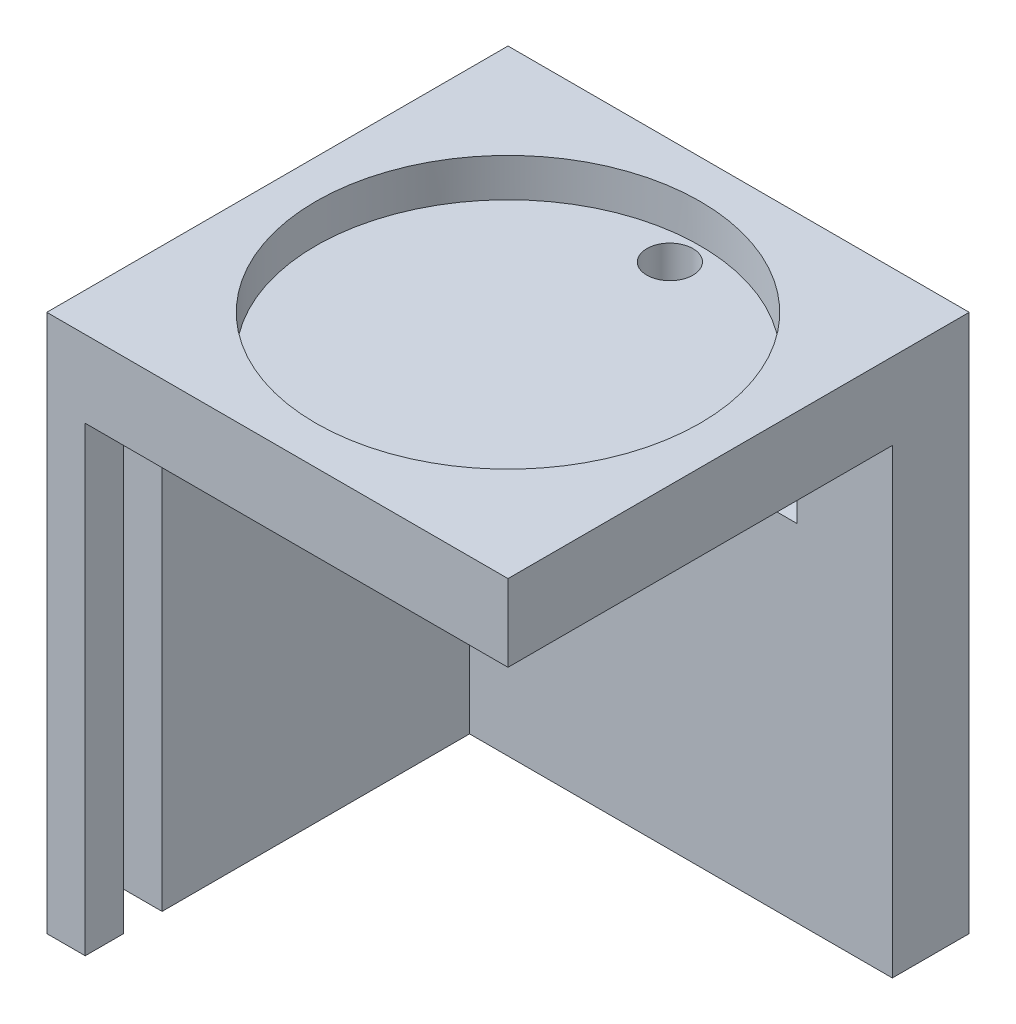
SolidWorks part; units mm, degrees
ref_plane "정면" through (0, 0, 0) normal (0, 0, 1) x (1, 0, 0)
ref_plane "윗면" through (0, 0, 0) normal (0, 1, 0) x (1, 0, 0)
ref_plane "우측면" through (0, 0, 0) normal (1, 0, 0) x (0, 0, -1)
sketch "Sketch1" plane through (0, 0, 0) normal (0, 1, 0) x (1, 0, 0)
  line L1 (0, 0) -> (670, 0)
  line L2 (0, 0) -> (0, 120)
  line L3 (0, 120) -> (670, 120)
  line L4 (670, 0) -> (670, 120)
  dimension "700" = 670
  dimension "D2" = 120
extrude "Boss-Extrude1" add sketch "Sketch1" along normal blind 530
sketch "Sketch2" plane through (0, 0, 0) normal (0, 0, 1) x (1, 0, 0)
  line L0 (0, 530) -> (0, 0) construction
  line L1 (10, 280) -> (110, 280)
  line L2 (10, 280) -> (10, 480)
  line L3 (10, 480) -> (110, 480)
  line L4 (110, 280) -> (110, 480)
  line L5 (0, 0) -> (670, 0) construction
  line L6 (120, 280) -> (120, 480)
  line L7 (120, 280) -> (220, 280)
  line L8 (220, 280) -> (220, 480)
  line L9 (120, 480) -> (220, 480)
  line L10 (230, 280) -> (230, 480)
  line L11 (230, 280) -> (330, 280)
  line L12 (330, 280) -> (330, 480)
  line L13 (230, 480) -> (330, 480)
  line L14 (340, 280) -> (340, 480)
  line L15 (340, 280) -> (440, 280)
  line L16 (440, 280) -> (440, 480)
  line L17 (340, 480) -> (440, 480)
  line L18 (450, 280) -> (450, 480)
  line L19 (450, 280) -> (550, 280)
  line L20 (550, 280) -> (550, 480)
  line L21 (450, 480) -> (550, 480)
  line L22 (560, 280) -> (560, 480)
  line L23 (560, 280) -> (660, 280)
  line L24 (660, 280) -> (660, 480)
  line L25 (560, 480) -> (660, 480)
  line L27 (10, 10) -> (660, 10)
  line L28 (10, 10) -> (10, 260)
  line L29 (10, 260) -> (660, 260)
  line L30 (660, 10) -> (660, 260)
  line L31 (0, 530) -> (670, 530) construction
  point P6 (10, 380)
  dimension "D1" = 100
  dimension "D2" = 200
  dimension "D3" = 10
  dimension "D4" = 50
  dimension "D6" = 10
  dimension "D7" = 20
  dimension "D5" = 6
extrude "Cut-Extrude1" cut sketch "Sketch2" against normal blind 100
sketch "Sketch3" plane through (0, 530, 0) normal (0, 1, 0) x (1, 0, 0)
  line L1 (670, 120) -> (0, 120) construction
  line L2 (0, 120) -> (0, 0) construction
  circle A0 centre (60, 60) radius 50
  circle A1 centre (170, 60) radius 50
  circle A2 centre (280, 60) radius 50
  circle A3 centre (390, 60) radius 50
  circle A4 centre (500, 60) radius 50
  circle A5 centre (610, 60) radius 50
  dimension "D1" = 100
  dimension "D2" = 10
  dimension "D3" = 10
  dimension "D4" = 6
extrude "Cut-Extrude2" cut sketch "Sketch3" against normal blind 260
hole_wizard "Ø12.0 (12) Diameter Hole2" positions "3DSketch1" profile "Sketch7" hole size "Ø12.0" standard "Ansi Metric"
sketch3d "3DSketch1"
  point P0 (59.7046, 270, -102.4117)
  point P2 (171.5567, 270, -102.6076)
  point P4 (280.8723, 270, -102.3969)
  point P6 (391.0687, 270, -102.7535)
  point P8 (500.7133, 270, -101.754)
  point P10 (609.5165, 270, -101.1227)
sketch "Sketch7" plane through (59.7046, 270, -102.4117) normal (1, 0, 0) x (0, 0, 1)
  line L0 (0, 0) -> (0, 33.6052)
  line L1 (0, 33.6052) -> (6, 30)
  line L2 (6, 30) -> (6, 0)
  line L5 (6, 0) -> (0, 0)
  line L10 (0, 33.6052) -> (-6, 30) construction
  line L11 (0, -6.35) -> (0, 107.95) construction
  dimension "구멍 지름" = 12
  dimension "구멍 깊이" = 30
  dimension "드릴 각도" = 118
sketch "Sketch8" plane through (0, 0, 0) normal (0, 0, 1) x (1, 0, 0)
  line L0 (660, 280) -> (660, 480) construction
  line L1 (10, 280) -> (660, 280)
  line L2 (10, 280) -> (10, 330)
  line L3 (10, 330) -> (660, 330)
  line L4 (660, 280) -> (660, 330)
  dimension "D1" = 50
extrude "Boss-Extrude2" add sketch "Sketch8" against normal blind 5
sketch "Sketch9" plane through (670, 0, 0) normal (1, 0, 0) x (0, 0, -1)
  line L0 (0, 530) -> (0, 0) construction
  line L1 (10, 10) -> (20, 10)
  line L2 (10, 10) -> (10, 260)
  line L3 (10, 260) -> (20, 260)
  line L4 (20, 10) -> (20, 260)
  line L5 (0, 0) -> (120, 0) construction
  dimension "D1" = 10
  dimension "D2" = 10
  dimension "D3" = 10
  dimension "D4" = 250
extrude "Cut-Extrude3" cut sketch "Sketch9" against normal blind 717
sketch "Sketch10" plane through (0, 10, 0) normal (0, 1, 0) x (1, 0, 0)
  line L0 (670, 120) -> (0, 120) construction
  line L1 (365, 61.9436) -> (350, 87.9243)
  line L2 (350, 87.9243) -> (320, 87.9243)
  line L3 (320, 87.9243) -> (305, 61.9436)
  line L4 (305, 61.9436) -> (320, 35.9628)
  line L5 (320, 35.9628) -> (350, 35.9628)
  line L6 (350, 35.9628) -> (365, 61.9436)
  line L7 (0, 120) -> (0, 0) construction
  circle A0 centre (335, 61.9436) radius 25.9808 construction
  dimension "D1" = 60
  dimension "D2" = 305
extrude "Cut-Extrude4" cut sketch "Sketch10" against normal blind 5
sketch "Sketch11" plane through (0, 0, -100) normal (0, 0, 1) x (1, 0, 0)
  line L0 (10, 10) -> (660, 10) construction
  line L1 (250, 10) -> (260, 10)
  line L2 (250, 10) -> (250, 110)
  line L3 (250, 110) -> (260, 110)
  line L4 (260, 10) -> (260, 110)
  line L5 (660, 10) -> (660, 260) construction
  line L6 (410, 10) -> (420, 10)
  line L7 (410, 10) -> (410, 110)
  line L8 (410, 110) -> (420, 110)
  line L9 (420, 10) -> (420, 110)
  line L10 (25, 198.4569) -> (325, 145.5588)
  line L11 (325, 145.5588) -> (325, 122.0178)
  line L12 (325, 122.0178) -> (345, 122.0178)
  line L13 (345, 122.0178) -> (345, 145.5588)
  line L14 (345, 145.5588) -> (645, 198.4569)
  line L15 (645, 198.4569) -> (25, 198.4569)
  point P18 (345, 133.7883)
  dimension "D1" = 10
  dimension "D2" = 10
  dimension "D3" = 100
  dimension "D4" = 100
  dimension "D5" = 150
  dimension "D6" = 240
  dimension "D7" = 20
  dimension "D8" = 65
  dimension "D9" = 100
  dimension "D10" = 620
  dimension "D11" = 100
extrude "Boss-Extrude3" add sketch "Sketch11" along normal blind 78 separate body
sketch "Sketch12" plane through (0, 0, -100) normal (0, 0, 1) x (1, 0, 0)
  line L0 (660, 260) -> (10, 260) construction
  line L1 (75.1986, 260) -> (95.1986, 260)
  line L2 (75.1986, 260) -> (75.1986, 230)
  line L3 (75.1986, 230) -> (95.1986, 230)
  line L4 (95.1986, 260) -> (95.1986, 230)
  line L5 (65.1986, 260) -> (65.1986, 240) construction
  line L6 (185.1986, 260) -> (185.1986, 230)
  line L7 (185.1986, 260) -> (205.1986, 260)
  line L8 (205.1986, 260) -> (205.1986, 230)
  line L9 (185.1986, 230) -> (205.1986, 230)
  line L10 (295.1986, 260) -> (295.1986, 230)
  line L11 (295.1986, 260) -> (315.1986, 260)
  line L12 (315.1986, 260) -> (315.1986, 230)
  line L13 (295.1986, 230) -> (315.1986, 230)
  line L14 (405.1986, 260) -> (405.1986, 230)
  line L15 (405.1986, 260) -> (425.1986, 260)
  line L16 (425.1986, 260) -> (425.1986, 230)
  line L17 (405.1986, 230) -> (425.1986, 230)
  line L18 (515.1986, 260) -> (515.1986, 230)
  line L19 (515.1986, 260) -> (535.1986, 260)
  line L20 (535.1986, 260) -> (535.1986, 230)
  line L21 (515.1986, 230) -> (535.1986, 230)
  line L22 (625.1986, 260) -> (625.1986, 230)
  line L23 (625.1986, 260) -> (645.1986, 260)
  line L24 (645.1986, 260) -> (645.1986, 230)
  line L25 (625.1986, 230) -> (645.1986, 230)
  dimension "D1" = 20
  dimension "D2" = 30
  dimension "D3" = 10
  dimension "D4" = 6
extrude "Cut-Extrude5" cut sketch "Sketch12" against normal blind 80
sketch "Sketch15" plane through (345, 0, 0) normal (1, 0, 0) x (0, 0, -1)
  line L0 (20, 10) -> (20, 260) construction
  line L1 (20, 121.4638) -> (50, 121.4638)
  line L2 (20, 121.4638) -> (20, 145)
  line L3 (20, 145) -> (50, 145)
  line L4 (50, 121.4638) -> (50, 145)
  line L5 (120, 530) -> (120, 0) construction
  line L6 (100, 116.0134) -> (70, 116.0134)
  line L7 (100, 116.0134) -> (100, 145)
  line L8 (100, 145) -> (70, 145)
  line L9 (70, 116.0134) -> (70, 145)
  line L10 (20, 260) -> (10, 260) construction
  dimension "D1" = 20
  dimension "D2" = 20
  dimension "D3" = 115
  dimension "D4" = 30
extrude "Cut-Extrude7" cut sketch "Sketch15" against normal blind 35
shell "Shell1" thickness 3
sketch "Sketch16" plane through (0, 122.0178, 0) normal (0, -1, 0) x (1, 0, 0)
  line L0 (345, -50) -> (325, -50) construction
  line L1 (328, -53) -> (342, -53)
  line L2 (328, -53) -> (328, -67)
  line L3 (328, -67) -> (342, -67)
  line L4 (342, -53) -> (342, -67)
  line L5 (325, -50) -> (325, -70) construction
  line L6 (345, -50) -> (345, -70) construction
  line L7 (325, -70) -> (345, -70) construction
  dimension "D1" = 3
  dimension "D2" = 3
  dimension "D3" = 3
  dimension "D4" = 3
extrude "Cut-Extrude8" cut sketch "Sketch16" against normal blind 35
sketch "Sketch17" plane through (0, 0, 0) normal (0, 0, 1) x (1, 0, 0)
  text T0 "<b>DIFF_USER</b>" font "Britannic Bold" height in points 72
extrude "Boss-Extrude4" add sketch "Sketch17" along normal blind 5
sketch "Sketch18" plane through (0, 0, 0) normal (0, 0, 1) x (1, 0, 0)
  line L0 (0, 530) -> (670, 530) construction
  line L1 (0, 530) -> (670, 530)
  line L2 (0, 530) -> (0, 280)
  line L3 (0, 280) -> (670, 280)
  line L4 (670, 530) -> (670, 280)
  line L5 (670, 530) -> (670, 0) construction
  line L6 (0, 0) -> (670, 0) construction
  dimension "D1" = 280
extrude "Cut-Extrude10" cut sketch "Sketch18" against normal through all both and the other way through all
delete or keep bodies "Body-Delete/Keep 1" type delete bodies bodies 112
delete or keep bodies "Body-Delete/Keep 2" type delete bodies bodies 109
delete or keep bodies "Body-Delete/Keep 3" type delete bodies bodies 115
sketch "Sketch19" plane through (0, 0, -100) normal (0, 0, 1) x (1, 0, 0)
  line L0 (670, 280) -> (0, 280) construction
  line L1 (0, 0) -> (120, 0)
  line L2 (0, 0) -> (0, 280)
  line L3 (0, 280) -> (120, 280)
  line L4 (120, 0) -> (120, 280)
  line L5 (670, 280) -> (670, 0) construction
  line L6 (120, 280) -> (670, 280)
  line L7 (120, 280) -> (120, 0)
  line L8 (120, 0) -> (670, 0)
  line L9 (670, 280) -> (670, 0)
  line L10 (670, 0) -> (0, 0) construction
  dimension "D1" = 120
extrude "Cut-Extrude11" cut sketch "Sketch19" against normal through all both and the other way through all contours L9 L6 L4 L8
sketch "Sketch20" plane through (0, 0, -100) normal (0, 0, 1) x (1, 0, 0)
  line L0 (120, 260) -> (120, 10) construction
  line L1 (0, 0) -> (120, 0)
  line L2 (0, 0) -> (0, 140)
  line L3 (0, 140) -> (120, 140)
  line L4 (120, 0) -> (120, 140)
  dimension "D1" = 140
extrude "Cut-Extrude12" cut sketch "Sketch20" against normal through all both and the other way through all
